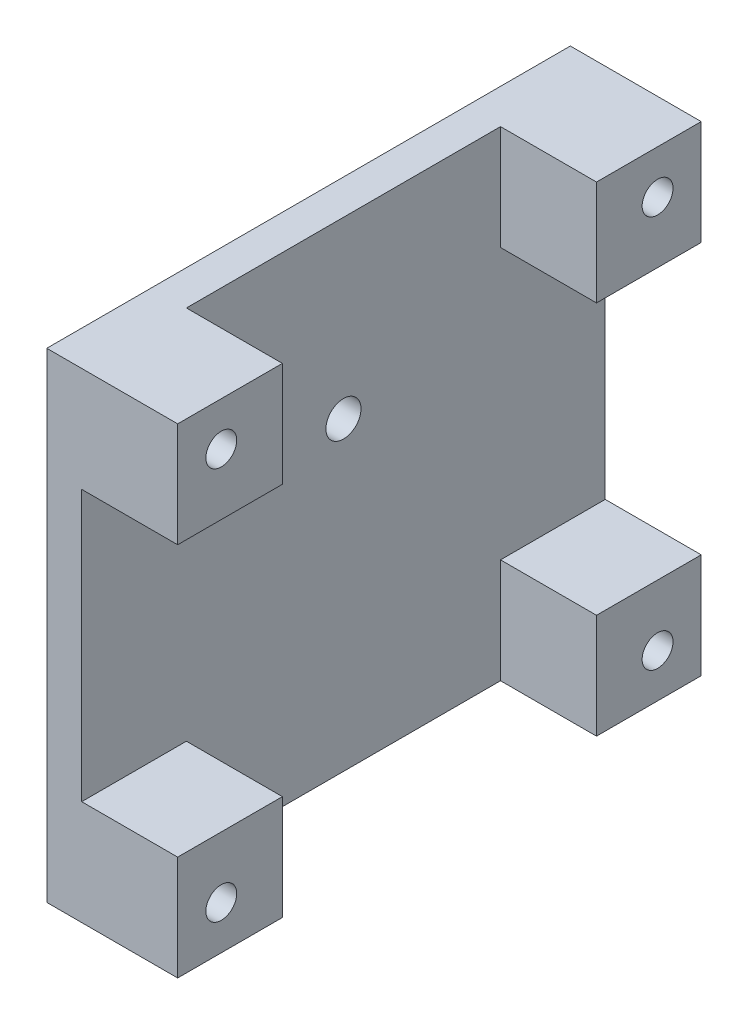
SolidWorks part; units mm, degrees
ref_plane "Front Plane" through (0, 0, 0) normal (0, 0, 1) x (1, 0, 0)
ref_plane "Top Plane" through (0, 0, 0) normal (0, 1, 0) x (1, 0, 0)
ref_plane "Right Plane" through (0, 0, 0) normal (1, 0, 0) x (0, 0, -1)
sketch "Sketch1" plane through (0, 0, 0) normal (1, 0, 0) x (0, 0, -1)
  line L1 (-38.1, -34.925) -> (38.1, -34.925)
  line L2 (-38.1, -34.925) -> (-38.1, 34.925)
  line L3 (-38.1, 34.925) -> (38.1, 34.925)
  line L4 (38.1, -34.925) -> (38.1, 34.925)
  line L5 (-38.1, -34.925) -> (38.1, 34.925) construction
  line L6 (-38.1, 34.925) -> (38.1, -34.925) construction
  point P0 (0, 0)
  dimension "D1" = 76.2
  dimension "D2" = 69.85
extrude "Boss-Extrude1" add sketch "Sketch1" along normal blind 19.05
sketch "Sketch2" plane through (19.05, 0, 0) normal (1, 0, 0) x (0, 0, -1)
  line L0 (38.1, 34.925) -> (-38.1, 34.925) construction
  line L1 (-22.86, -34.925) -> (22.86, -34.925)
  line L2 (-22.86, -34.925) -> (-22.86, -19.685)
  line L3 (-22.86, 34.925) -> (22.86, 34.925)
  line L4 (22.86, -34.925) -> (22.86, -19.685)
  line L5 (-22.86, -34.925) -> (22.86, 34.925) construction
  line L6 (-22.86, 34.925) -> (22.86, -34.925) construction
  line L7 (-38.1, 34.925) -> (-38.1, -34.925) construction
  line L8 (38.1, -34.925) -> (38.1, 34.925) construction
  line L9 (-38.1, 19.685) -> (-22.86, 19.685)
  line L10 (-38.1, 19.685) -> (-38.1, -19.685)
  line L11 (-38.1, -19.685) -> (-22.86, -19.685)
  line L12 (38.1, 19.685) -> (38.1, -19.685)
  line L13 (-22.86, 19.685) -> (-22.86, 34.925)
  line L14 (22.86, 19.685) -> (38.1, 19.685)
  line L15 (22.86, -19.685) -> (38.1, -19.685)
  line L16 (22.86, 19.685) -> (22.86, 34.925)
  point P0 (0, 0)
  dimension "D1" = 15.24
  dimension "D2" = 15.24
extrude "Cut-Extrude1" cut sketch "Sketch2" against normal blind 13.97
hole_wizard "CBORE for #8 Socket Head Cap Screw1" positions "Sketch6" profile "Sketch5" counterbore size "#8" standard "ANSI Inch" end condition through all
sketch "Sketch6" plane through (0, -5.7484, -9.1222) normal (1, 0, 0) x (0, 0, -1)
  line L3 (-9.1222, 5.7484) -> (-62.6267, 5.7484) construction
  line L5 (-9.1222, 5.7484) -> (-9.1222, 58.2596) construction
  point P0 (-40.8722, 34.3234)
  point P14 (22.6278, 34.3234)
  point P16 (22.6278, -22.8266)
  point P18 (-40.8722, -22.8266)
  dimension "D3" = 63.5
  dimension "D4" = 57.15
sketch "Sketch5" plane through (0, 28.575, 31.75) normal (0, 1, 0) x (0, 0, 1)
  line L0 (0, 0) -> (0, 19.05)
  line L1 (0, 19.05) -> (2.2479, 19.05)
  line L3 (2.2479, 19.05) -> (2.2479, 4.1656)
  line L4 (2.2479, 4.1656) -> (3.9688, 4.1656)
  line L5 (3.9688, 4.1656) -> (3.9688, 0)
  line L7 (3.9688, 0) -> (0, 0)
  line L11 (0, -6.35) -> (0, 107.95) construction
  dimension "Thru Hole Dia." = 4.4958
  dimension "Thru Hole Depth" = 19.05
  dimension "C'Bore Dia." = 7.9375
  dimension "C'Bore Depth" = 4.1656
hole_wizard "1/4-20 Tapped Hole1" positions "Sketch4" profile "Sketch3" tap size "1/4-20" standard "ANSI Inch"
sketch "Sketch4" plane through (5.08, 0, 0) normal (1, 0, 0) x (0, 0, -1)
  circle A1 centre (-31.75, 28.575) radius 3.9688 construction
  point P0 (0, 9.525)
  dimension "D1" = 19.05
sketch "Sketch3" plane through (5.08, 9.525, 0) normal (0, 1, 0) x (0, 0, -1)
  line L0 (0, 0) -> (0, 20.5838)
  line L1 (0, 20.5838) -> (2.5527, 19.05)
  line L2 (2.5527, 19.05) -> (2.5527, 0)
  line L5 (2.5527, 0) -> (0, 0)
  line L10 (0, 20.5838) -> (-2.5527, 19.05) construction
  line L11 (0, -6.35) -> (0, 107.95) construction
  dimension "Tap Drill Dia." = 5.1054
  dimension "Tap Drill Depth" = 19.05
  dimension "Drill Angle" = 118
cosmetic thread "Hole Thread1"
